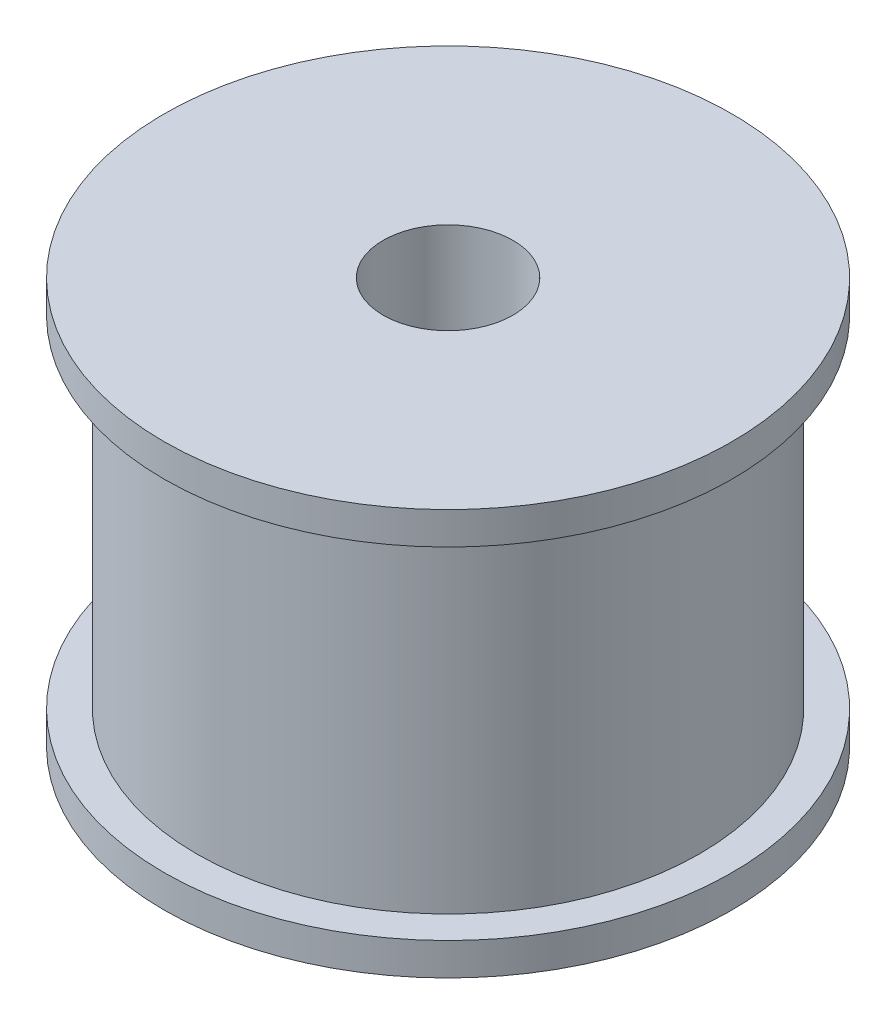
SolidWorks part; units mm, degrees
ref_plane "Front Plane" through (0, 0, 0) normal (0, 0, 1) x (1, 0, 0)
ref_plane "Top Plane" through (0, 0, 0) normal (0, 1, 0) x (1, 0, 0)
ref_plane "Right Plane" through (0, 0, 0) normal (1, 0, 0) x (0, 0, -1)
sketch "Sketch1" plane through (0, 0, 0) normal (0, 1, 0) x (1, 0, 0)
  circle A0 centre (0, 0) radius 17.5
  dimension "D1" = 35
extrude "Boss-Extrude1" add sketch "Sketch1" along normal blind 2
sketch "Sketch2" plane through (0, 2, 0) normal (0, 1, 0) x (1, 0, 0)
  circle A0 centre (0, 0) radius 15.5
  dimension "D1" = 31
extrude "Boss-Extrude2" add sketch "Sketch2" along normal blind 21
sketch "Sketch3" plane through (0, 23, 0) normal (0, 1, 0) x (1, 0, 0)
  circle A0 centre (0, 0) radius 17.5
  dimension "D1" = 35
extrude "Boss-Extrude3" add sketch "Sketch3" along normal blind 2
sketch "Sketch4" plane through (0, 25, 0) normal (0, 1, 0) x (1, 0, 0)
  circle A0 centre (0, 0) radius 4
  dimension "D1" = 8
extrude "Cut-Extrude1" cut sketch "Sketch4" against normal through all
